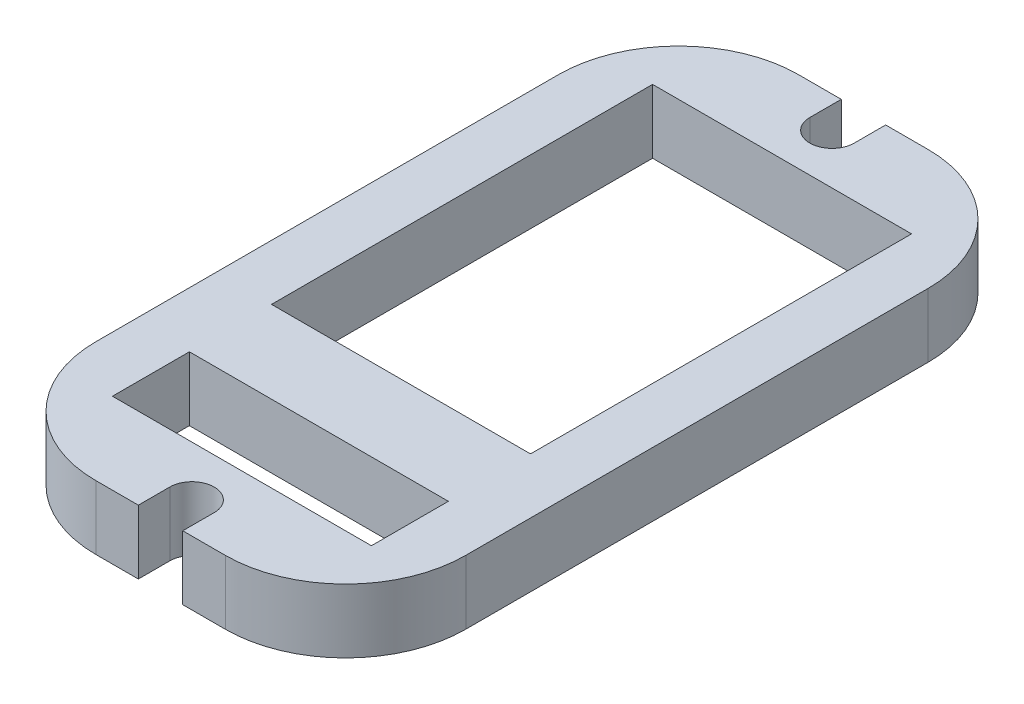
SolidWorks part; units mm, degrees
ref_plane "Front Plane" through (0, 0, 0) normal (0, 0, 1) x (1, 0, 0)
ref_plane "Top Plane" through (0, 0, 0) normal (0, 1, 0) x (1, 0, 0)
ref_plane "Right Plane" through (0, 0, 0) normal (1, 0, 0) x (0, 0, -1)
sketch "Sketch2" plane through (0, 0, 0) normal (0, 1, 0) x (1, 0, 0)
  line L0 (-0.6, 9.5) -> (-1.75, 9.5)
  line L1 (-5, 6.25) -> (-5, -6.25)
  line L2 (-1.75, -9.5) -> (-0.6, -9.5)
  line L3 (-3.5, -3) -> (3.5, -3)
  line L4 (3.5, -3) -> (3.5, 7.3)
  line L5 (3.5, 7.3) -> (-3.5, 7.3)
  line L6 (-3.5, 7.3) -> (-3.5, -3)
  line L7 (-3.5, -7.3) -> (3.5, -7.3)
  line L8 (3.5, -7.3) -> (3.5, -5.22)
  line L9 (3.5, -5.22) -> (-3.5, -5.22)
  line L10 (-3.5, -5.22) -> (-3.5, -7.3)
  line L11 (0, 8.65) -> (0, -8.65) construction
  line L12 (-0.6, -8.65) -> (-0.6, -9.5)
  line L13 (0.6, -8.65) -> (0.6, -9.5)
  line L14 (-0.6, 9.5) -> (-0.6, 8.65)
  line L15 (0.6, -9.5) -> (1.75, -9.5)
  line L16 (5, -6.25) -> (5, 6.25)
  line L17 (1.75, 9.5) -> (0.6, 9.5)
  line L18 (0, 0) -> (0, -3) construction
  line L19 (0, -3) -> (0, -5.22) construction
  line L20 (0.6, 9.5) -> (0.6, 8.65)
  arc A0 (-0.6, 8.65) -> (0.6, 8.65) centre (0, 8.65) ccw
  arc A1 (0.6, -8.65) -> (-0.6, -8.65) centre (0, -8.65) ccw
  arc A2 (-1.75, 9.5) -> (-5, 6.25) centre (-1.75, 6.25) ccw
  arc A3 (-5, -6.25) -> (-1.75, -9.5) centre (-1.75, -6.25) ccw
  arc A4 (1.75, -9.5) -> (5, -6.25) centre (1.75, -6.25) ccw
  arc A5 (5, 6.25) -> (1.75, 9.5) centre (1.75, 6.25) ccw
  point P30 (0, -5.22)
  point P31 (0, -3)
  point P38 (0, 0)
  dimension "D7" = 0.6
  dimension "D9" = 3.25
  dimension "D1" = 2.22
  dimension "D2" = 3
  dimension "D3" = 10.3
  dimension "D4" = 2.08
  dimension "D5" = 17.3
  dimension "D6" = 7
  dimension "D8" = 10
  dimension "D10" = 19
extrude "Boss-Extrude1" add sketch "Sketch2" along normal blind 1.73
